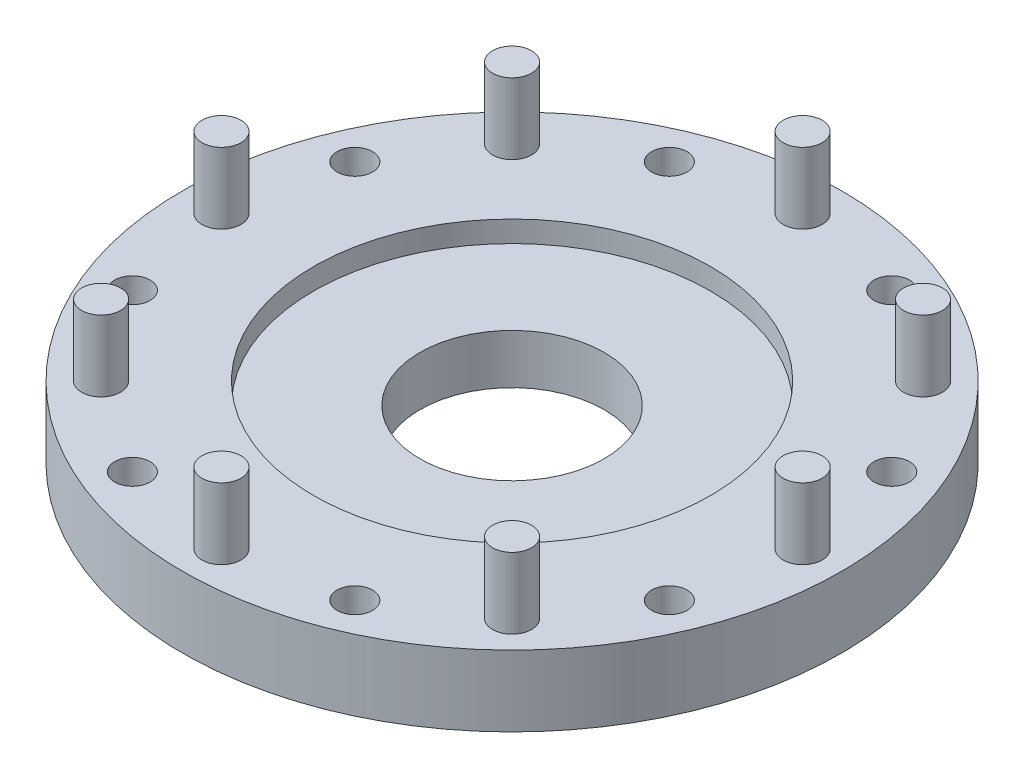
SolidWorks part; units mm, degrees
material "ABS"
ref_plane "Front Plane" through (0, 0, 0) normal (0, 0, 1) x (1, 0, 0)
ref_plane "Top Plane" through (0, 0, 0) normal (0, 1, 0) x (1, 0, 0)
ref_plane "Right Plane" through (0, 0, 0) normal (1, 0, 0) x (0, 0, -1)
sketch "Sketch1" plane through (0, 0, 0) normal (0, 0, 1) x (1, 0, 0)
  line L0 (0, -1.7519) -> (0, 48.3018) construction
  line L1 (-28, 10) -> (-46.5, 10)
  line L4 (-46.5, 10) -> (-46.5, 0)
  line L5 (-46.5, 0) -> (-13, 0)
  line L6 (-13, 0) -> (-13, 7)
  line L7 (-13, 7) -> (-28, 7)
  line L8 (-28, 7) -> (-28, 10)
  dimension "D1" = 46.5
  dimension "D3" = 3
  dimension "D2" = 28
  dimension "D4" = 13
  dimension "D5" = 10
revolve "Revolve1" add sketch "Sketch1" angle 360 about L0
sketch "Sketch2" plane through (0, 10, 0) normal (0, 1, 0) x (1, 0, 0)
  line L0 (0, 41) -> (0, 0) construction
  line L1 (0, 0) -> (15.69, 37.8791) construction
  circle A0 centre (0, 0) radius 41 construction
  circle A1 centre (0, 41) radius 2.75
  circle A2 centre (15.69, 37.8791) radius 2.5
  circle A3 centre (28.9914, 28.9914) radius 2.75
  circle A4 centre (37.8791, 15.69) radius 2.5
  circle A5 centre (41, 0) radius 2.75
  circle A6 centre (37.8791, -15.69) radius 2.5
  circle A7 centre (28.9914, -28.9914) radius 2.75
  circle A8 centre (15.69, -37.8791) radius 2.5
  circle A9 centre (0, -41) radius 2.75
  circle A10 centre (-15.69, -37.8791) radius 2.5
  circle A11 centre (-28.9914, -28.9914) radius 2.75
  circle A12 centre (-37.8791, -15.69) radius 2.5
  circle A13 centre (-41, 0) radius 2.75
  circle A14 centre (-37.8791, 15.69) radius 2.5
  circle A15 centre (-28.9914, 28.9914) radius 2.75
  circle A16 centre (-15.69, 37.8791) radius 2.5
  point P37 (0, 0)
  dimension "D1" = 82
  dimension "D2" = 5.5
  dimension "D3" = 5
  dimension "D4" = 22.5
  dimension "D5" = 8
extrude "Cut-Extrude1" cut sketch "Sketch2" against normal through all both and the other way through all
sketch "Sketch3" plane through (0, 0, 0) normal (0, 0, 1) x (1, 0, 0)
  line L0 (28.5, 4) -> (28.5, 0)
  line L2 (28.5, 0) -> (21.5, 0)
  line L3 (21.5, 0) -> (21.5, 4)
  line L6 (25, 4) -> (25, 0) construction
  line L7 (0, -19.0654) -> (0, 22.7714) construction
  line L8 (-46.5, 0) -> (46.5, 0) construction
  line L9 (28.5, 4) -> (21.5, 4)
  dimension "D1" = 25
  dimension "D2" = 4
  dimension "D3" = 7
revolve "Cut-Revolve1" cut sketch "Sketch3" angle 360 about L7
sketch "Sketch4" plane through (0, 0, 0) normal (0, -1, 0) x (1, 0, 0)
  line L0 (-19.69, 40.1885) -> (-19.69, 35.5697)
  line L1 (-19.69, 35.5697) -> (-15.69, 33.2603)
  line L2 (-15.69, 33.2603) -> (-11.69, 35.5697)
  line L3 (-11.69, 35.5697) -> (-11.69, 40.1885)
  line L4 (-11.69, 40.1885) -> (-15.69, 42.4979)
  line L5 (-15.69, 42.4979) -> (-19.69, 40.1885)
  line L6 (-15.69, 42.4979) -> (-15.69, 33.2603) construction
  line L7 (18.956, 41.145) -> (14.4946, 42.3405)
  line L8 (14.4946, 42.3405) -> (11.2286, 39.0745)
  line L9 (11.2286, 39.0745) -> (12.424, 34.6131)
  line L10 (12.424, 34.6131) -> (16.8855, 33.4176)
  line L11 (16.8855, 33.4176) -> (20.1514, 36.6836)
  line L12 (20.1514, 36.6836) -> (18.956, 41.145)
  line L13 (42.4979, 15.69) -> (40.1885, 19.69)
  line L14 (40.1885, 19.69) -> (35.5697, 19.69)
  line L15 (35.5697, 19.69) -> (33.2603, 15.69)
  line L16 (33.2603, 15.69) -> (35.5697, 11.69)
  line L17 (35.5697, 11.69) -> (40.1885, 11.69)
  line L18 (40.1885, 11.69) -> (42.4979, 15.69)
  line L19 (41.145, -18.956) -> (42.3405, -14.4946)
  line L20 (42.3405, -14.4946) -> (39.0745, -11.2286)
  line L21 (39.0745, -11.2286) -> (34.6131, -12.424)
  line L22 (34.6131, -12.424) -> (33.4176, -16.8855)
  line L23 (33.4176, -16.8855) -> (36.6836, -20.1514)
  line L24 (36.6836, -20.1514) -> (41.145, -18.956)
  line L25 (15.69, -42.4979) -> (19.69, -40.1885)
  line L26 (19.69, -40.1885) -> (19.69, -35.5697)
  line L27 (19.69, -35.5697) -> (15.69, -33.2603)
  line L28 (15.69, -33.2603) -> (11.69, -35.5697)
  line L29 (11.69, -35.5697) -> (11.69, -40.1885)
  line L30 (11.69, -40.1885) -> (15.69, -42.4979)
  line L31 (-18.956, -41.145) -> (-14.4946, -42.3405)
  line L32 (-14.4946, -42.3405) -> (-11.2286, -39.0745)
  line L33 (-11.2286, -39.0745) -> (-12.424, -34.6131)
  line L34 (-12.424, -34.6131) -> (-16.8855, -33.4176)
  line L35 (-16.8855, -33.4176) -> (-20.1514, -36.6836)
  line L36 (-20.1514, -36.6836) -> (-18.956, -41.145)
  line L37 (-42.4979, -15.69) -> (-40.1885, -19.69)
  line L38 (-40.1885, -19.69) -> (-35.5697, -19.69)
  line L39 (-35.5697, -19.69) -> (-33.2603, -15.69)
  line L40 (-33.2603, -15.69) -> (-35.5697, -11.69)
  line L41 (-35.5697, -11.69) -> (-40.1885, -11.69)
  line L42 (-40.1885, -11.69) -> (-42.4979, -15.69)
  line L43 (-41.145, 18.956) -> (-42.3405, 14.4946)
  line L44 (-42.3405, 14.4946) -> (-39.0745, 11.2286)
  line L45 (-39.0745, 11.2286) -> (-34.6131, 12.424)
  line L46 (-34.6131, 12.424) -> (-33.4176, 16.8855)
  line L47 (-33.4176, 16.8855) -> (-36.6836, 20.1514)
  line L48 (-36.6836, 20.1514) -> (-41.145, 18.956)
  line L49 (11.2286, 39.0745) -> (20.1514, 36.6836) construction
  circle A0 centre (15.69, 37.8791) radius 2.5 construction
  circle A1 centre (0, 41) radius 2.75 construction
  circle A2 centre (0, 41) radius 2.75 construction
  circle A3 centre (15.69, 37.8791) radius 2.5 construction
  circle A4 centre (-15.69, 37.8791) radius 2.5 construction
  circle A5 centre (-15.69, 37.8791) radius 2.5 construction
  point P57 (0, 0)
  dimension "D1" = 120
  dimension "D2" = 120
  dimension "D3" = 8
  dimension "D4" = 8
extrude "Cut-Extrude2" cut sketch "Sketch4" against normal blind 5
sketch "Sketch5" plane through (0, 0, 0) normal (0, -1, 0) x (1, 0, 0)
  circle A0 centre (0, 41) radius 2.75 construction
  circle A1 centre (0, 41) radius 2.75
  circle A2 centre (28.9914, 28.9914) radius 2.75 construction
  circle A3 centre (41, 0) radius 2.75 construction
  circle A4 centre (28.9914, -28.9914) radius 2.75 construction
  circle A5 centre (0, -41) radius 2.75 construction
  circle A6 centre (-28.9914, -28.9914) radius 2.75 construction
  circle A7 centre (-41, 0) radius 2.75 construction
  circle A8 centre (-28.9914, 28.9914) radius 2.75 construction
  circle A9 centre (28.9914, 28.9914) radius 2.75
  circle A10 centre (41, 0) radius 2.75
  circle A11 centre (28.9914, -28.9914) radius 2.75
  circle A12 centre (0, -41) radius 2.75
  circle A13 centre (-28.9914, -28.9914) radius 2.75
  circle A14 centre (-41, 0) radius 2.75
  circle A15 centre (-28.9914, 28.9914) radius 2.75
extrude "Boss-Extrude1" add sketch "Sketch5" against normal blind 20
equation "\"Stator_OD\"= 60'No Tolerance given"
equation "\"A\"=35.81 'taken off spec sheet for 06808 (A)"
equation "\"Rotor_ID\"= 30'No Tolerance Given"
equation "\"back_bearing_Thickness\"= 5'-0.12"
equation "\"back_bearing_OD\"= 24'-0.009 https://www.mcmaster.com/5972K155/"
equation "\"Stator_Gap\"= 0.0375'+- 0.0125 (From 1.3.3.1 Kollmorgen manual)"
equation "\"Back_mount_hole\"= 1.75'To be tapped to M2 (USE LOCKTITE)"
equation "\"facePlate_Mount_Hole\"= 2.75'To be tapped to M3"
equation "\"final_shaftD\"= 12'To fit in harmonic"
equation "\"final_shaftL\"= 5.25+3+\"sheet_thick\"+\"connector_thick\"-3+\"harmon_coupleL\"+0.5-\"shaft_Ladjust\"'length to make everything nice and aligned"
equation "\"back_bearing_ID\"= 15'"
equation "\"back_bearing_IDOD\"= 16.5'measured off CAD, actually 16.75, but rounded down to nicer number"
equation "\"rotor_shaftD\"= \"Rotor_ID\" - (\"rotor-shaft_gap\")*2'"
equation "\"front_bearing_ID\"= 12'https://www.mcmaster.com/5972K154/"
equation "\"front_bearing_OD\"= 21'-0.009"
equation "\"front_bearing_IDOD\"= 13.5'Measured off CAD. Actually 13.75, but rounded down"
equation "\"rotor-shaft_gap\" = 0.0185 '+-0.0065 (from manual)"
equation "\"front_bearing_Thickness\"= 5'-0.12"
equation "\"rotor_thickness\"= 2.4'measured off CAD"
equation "\"rotor_height\"= 32.86'+-0.075 taken off spec sheet for 06826 (C)"
equation "\"B\"= 26.3'+-0.35 taken off spec sheet for 06826"
equation "\"key_L\"= 20'-0.2 https://www.mcmaster.com/2977N19/"
equation "\"key_H\"= 4'-0.03"
equation "\"key_W\"= 4'-0.03"
equation "\"harmon_keyH\"= 13.8'+0.1 from drawing"
equation "\"harmon_coupleL\"= 21.5' taken from drawing https://www.harmonicdrive.net/_hd/content/caddownloads/dxf/csg-2uh-lw_gearheads/csg-20-100-2uh-lw.pdf"
equation "\"harmon_diam\"= 93' from drawing"
equation "\"harmon_BCD\"= 82' from drawing"
equation "\"harmon_holeD1\"= 5.5' from drawing"
equation "\"harmon_holeD2\"= 5' from drawing"
equation "\"harmon_holeAng\"= 22.5' from drawing"
equation "\"sheet_thick\"= 1/8*25.4 'random, replace w actual sheet thickness when u feel like :)"
equation "\"D1@Sketch1\"=\"harmon_diam\"/2"
equation "\"D1@Sketch2\"=\"harmon_BCD\""
equation "\"D2@Sketch2\"=\"harmon_holeD1\""
equation "\"D3@Sketch2\"=\"harmon_holeD2\""
equation "\"D4@Sketch2\"=\"harmon_holeAng\""
equation "\"nut-thickness\"= 5 'idk measure the ones in the shop and adjust"
equation "\"D1@Cut-Extrude2\"=\"nut-thickness\""
equation "\"connector_thick\"= 10' random for now"
equation "\"D5@Sketch1\"=\"connector_thick\""
equation "\"shaft_Ladjust\"= 6.5' sorry. It's silly, but it works."
equation "\"D1@Boss-Extrude1\"=\"connector_thick\"+10"
